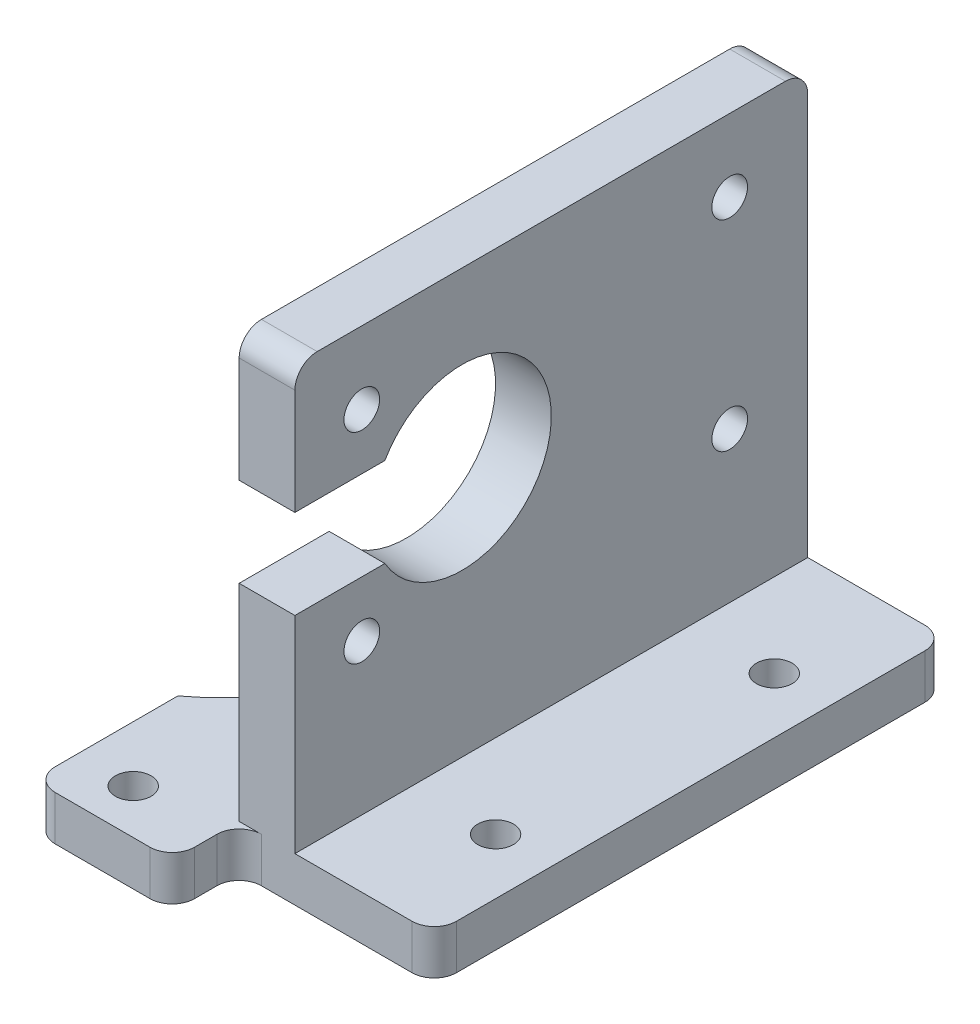
SolidWorks part; units mm, degrees
ref_plane "前视基准面" through (0, 0, 0) normal (0, 0, 1) x (1, 0, 0)
ref_plane "上视基准面" through (0, 0, 0) normal (0, 1, 0) x (1, 0, 0)
ref_plane "右视基准面" through (0, 0, 0) normal (1, 0, 0) x (0, 0, -1)
sketch "Sketch1" plane through (0, 0, 0) normal (1, 0, 0) x (0, 0, -1)
  line L0 (-23, 0.5) -> (23, 0.5) construction
  line L1 (-23, -16) -> (23, -16)
  line L2 (-23, -16) -> (-23, 16)
  line L3 (-23, 16) -> (23, 16)
  line L4 (23, -16) -> (23, 16)
  line L5 (-23, -16) -> (23, 16) construction
  line L6 (-23, 16) -> (23, -16) construction
  line L7 (-23, 9.5) -> (23, 9.5) construction
  circle A0 centre (16, 9.5) radius 1.6
  circle A1 centre (-17, 9.5) radius 1.6
  circle A2 centre (-8, 0.5) radius 8
  circle A3 centre (-17, -8.5) radius 1.6
  circle A4 centre (16, -8.5) radius 1.6
  point P0 (0, 0)
  point P8 (23, 0)
  dimension "D4" = 16
  dimension "D5" = 15
  dimension "D6" = 9
  dimension "D7" = 33
  dimension "D8" = 3.2
  dimension "D9" = 18
  dimension "D1" = 46
  dimension "D2" = 32
  dimension "D3" = 0.5
extrude "Extrude1" add sketch "Sketch1" along normal blind 5
sketch "Sketch2" plane through (5, 0, 0) normal (1, 0, 0) x (0, 0, -1)
  line L0 (-8, 0.5) -> (-23, 0.5) construction
  line L1 (-23, 16) -> (-23, -16) construction
  line L3 (-13, -3.5) -> (-23, -3.5)
  line L4 (-13, -3.5) -> (-13, 4.5)
  line L5 (-13, 4.5) -> (-23, 4.5)
  line L6 (-23, -3.5) -> (-23, 4.5)
  line L7 (-13, -3.5) -> (-23, 4.5) construction
  line L8 (-13, 4.5) -> (-23, -3.5) construction
  point P5 (-18, 0.5)
  dimension "D1" = 8
  dimension "D2" = 10
extrude "Extrude2" cut sketch "Sketch2" against normal through all
sketch "Sketch3" plane through (0, 0, 0) normal (0, 0, 1) x (1, 0, 0)
  line L0 (2.5, -16) -> (2.5, -50016) construction
  line L1 (5, -16) -> (0, -16) construction
  line L2 (0, -16) -> (0, -22)
  line L7 (0, -22) -> (-12.5, -22)
  line L8 (-12.5, -22) -> (-12.5, -26)
  line L9 (-12.5, -26) -> (17.5, -26)
  line L10 (17.5, -22) -> (17.5, -26)
  line L11 (5, -22) -> (17.5, -22)
  line L12 (5, -16) -> (5, -22)
  line L13 (0, -16) -> (5, -16)
  point P4 (2.5, -16)
  point P13 (2.5, -26)
  dimension "D1" = 6
  dimension "D2" = 10
  dimension "D3" = 15
extrude "Extrude3" add sketch "Sketch3" along normal mid plane 46
sketch "Sketch4" plane through (0, -22, 0) normal (0, 1, 0) x (1, 0, 0)
  line L0 (2.5, -23) -> (2.5, 49977) construction
  line L1 (5, -23) -> (0, -23) construction
  line L2 (0, 0) -> (50000, 0) construction
  circle A0 centre (-7.5, -12.5) radius 1.6
  circle A1 centre (12.5, -12.5) radius 1.6
  circle A2 centre (-7.5, 12.5) radius 1.6
  circle A3 centre (12.5, 12.5) radius 1.6
  point P4 (2.5, -23)
  dimension "D1" = 25
  dimension "D2" = 20
  dimension "D3" = 3.2
extrude "Extrude4" cut sketch "Sketch4" against normal through all
sketch "草图1" plane through (0, -26, 0) normal (0, -1, 0) x (1, 0, 0)
  line L0 (-12.5, 23) -> (-12.5, -23) construction
  line L1 (-12.5, -29) -> (0, -29)
  line L2 (-12.5, -29) -> (-12.5, 29)
  line L3 (-12.5, 29) -> (0, 29)
  line L4 (0, -29) -> (0, 29)
  line L5 (-12.5, -29) -> (0, 29) construction
  line L6 (-12.5, 29) -> (0, -29) construction
  line L7 (17.5, 0) -> (-22.6766, 0) construction
  line L8 (17.5, 23) -> (17.5, -23) construction
  line L9 (-7.5, -12.5) -> (-7.5, 12.5) construction
  circle A0 centre (-7.5, -25) radius 1.6
  circle A1 centre (-7.5, 25) radius 1.6
  point P4 (-6.25, 0)
  dimension "D2" = 3.2
  dimension "D3" = 50
  dimension "D1" = 12.5
  dimension "D4" = 58
extrude "凸台-拉伸1" add sketch "草图1" against normal up to surface (4 mm away) up to face at (-7.5, -22, -14.1)
sketch "草图2" plane through (0, -22, 0) normal (0, 1, 0) x (1, 0, 0)
  line L0 (17.5, 0) -> (-23.5928, 0) construction
  line L1 (17.5, -23) -> (17.5, 23) construction
  line L2 (-12.5, -29) -> (-12.5, 29) construction
  line L3 (-12.5, 16) -> (-12.5, -16)
  arc A0 (-12.5, 16) -> (-12.5, -16) centre (-24.5, 0) cw
  dimension "D1" = 20
  dimension "D2" = 12
extrude "切除-拉伸1" cut sketch "草图2" against normal blind 10
fillet "圆角1" radius 2 8 edges at (0, -24, 29) (-12.5, -24, -29) (0, -24, -29) (-12.5, -24, 29) (17.5, -24, -23) (17.5, -24, 23) (2.5, 16, 23) (2.5, 16, -23)
